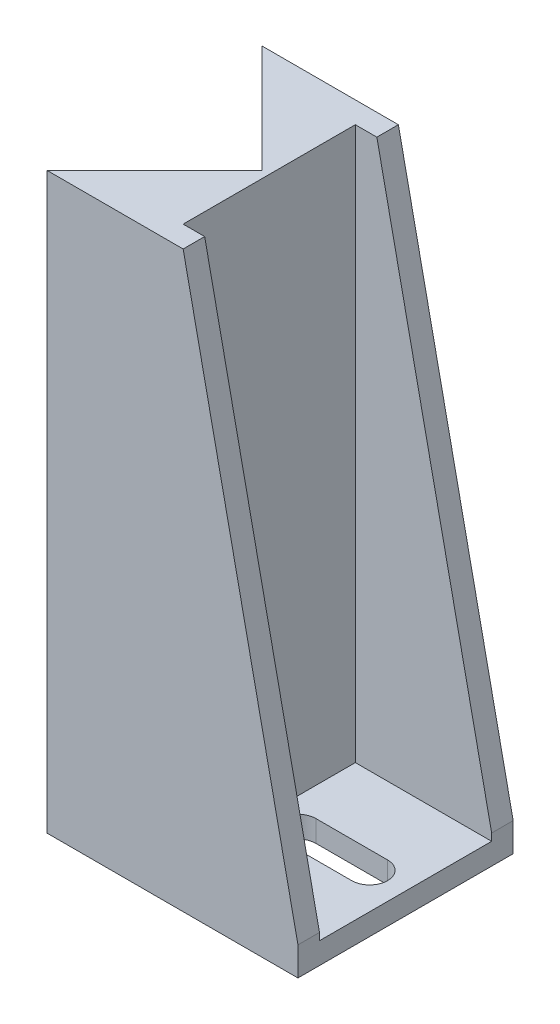
SolidWorks part; units mm, degrees
material "ABS"
ref_plane "Front Plane" through (0, 0, 0) normal (0, 0, 1) x (1, 0, 0)
ref_plane "Top Plane" through (0, 0, 0) normal (0, 1, 0) x (1, 0, 0)
ref_plane "Right Plane" through (0, 0, 0) normal (1, 0, 0) x (0, 0, -1)
sketch "Sketch1" plane through (0, 0, 0) normal (0, 0, 1) x (1, 0, 0)
  line L0 (0, 0) -> (25.4, 0)
  line L1 (25.4, 0) -> (25.4, 5.08)
  line L2 (25.4, 5.08) -> (5.08, 101.6)
  line L3 (5.08, 101.6) -> (0, 101.6)
  line L4 (0, 101.6) -> (0, 0)
  dimension "D1" = 25.4
  dimension "D2" = 5.08
  dimension "D3" = 101.6
extrude "Boss-Extrude1" add sketch "Sketch1" along normal blind 38.1
shell "Shell1" thickness 3.81
sketch "Sketch2" plane through (0, 0, 0) normal (0, -1, 0) x (1, 0, 0)
  line L0 (6.35, 19.05) -> (19.05, 19.05) construction
  line L1 (6.35, 22.225) -> (19.05, 22.225)
  line L2 (6.35, 15.875) -> (19.05, 15.875)
  line L4 (0, 38.1) -> (25.4, 38.1) construction
  line L5 (0, 38.1) -> (0, 0) construction
  arc A0 (6.35, 22.225) -> (6.35, 15.875) centre (6.35, 19.05) ccw
  arc A1 (19.05, 15.875) -> (19.05, 22.225) centre (19.05, 19.05) ccw
  point P2 (12.7, 19.05)
  point P12 (12.7, 38.1)
  point P16 (0, 19.05)
  dimension "D1" = 3.175
  dimension "D2" = 12.7
extrude "Cut-Extrude1" cut sketch "Sketch2" against normal up to surface (3.81 mm away) up to face at (12.7, 3.81, 19.05)
sketch "Sketch3" plane through (0, 101.6, 0) normal (0, 1, 0) x (1, 0, 0)
  line L0 (0, -19.05) -> (-19.05, 0)
  line L1 (0, -38.1) -> (0, 0) construction
  line L2 (-19.05, 0) -> (0, 0)
  line L3 (0, 0) -> (0, -38.1)
  line L4 (0, -38.1) -> (-19.05, -38.1)
  line L5 (-19.05, -38.1) -> (0, -19.05)
  line M5 (0, 0) -> (0, -38.1)
  dimension "D1" = 19.05
extrude "Boss-Extrude2" add sketch "Sketch3" against normal up to surface (101.6 mm away) contours L2 L0 M5 | L5 L4 M5 up to face at (12.7, 0, 19.05)
sketch "Sketch5" plane through (0, 101.6, 0) normal (0, 1, 0) x (1, 0, 0)
  line L0 (1.27, -3.81) -> (1.27, -34.29)
  line L1 (25.4, 0) -> (5.08, 0) construction
  line L3 (25.4, -3.81) -> (25.4, -34.29)
  line L4 (25.4, -38.1) -> (25.4, 0) construction
  line L5 (25.4, -34.29) -> (1.27, -34.29)
  line L6 (3.81, -34.29) -> (21.59, -34.29) construction
  line L7 (25.4, -3.81) -> (1.27, -3.81)
  dimension "D1" = 1.27
  dimension "D2" = 3.81
extrude "Cut-Extrude2" cut sketch "Sketch5" against normal up to surface (97.79 mm away) up to face at (12.7, 3.81, 25.9233)
sketch "Sketch6" plane through (0, 0, 0) normal (0, -1, 0) x (1, 0, 0)
  line L0 (-19.05, 0) -> (0, 19.05)
  line L1 (0, 19.05) -> (-19.05, 38.1)
  line L2 (-19.05, 38.1) -> (-19.05, 0)
extrude "Boss-Extrude3" add sketch "Sketch6" against normal blind 25.4
